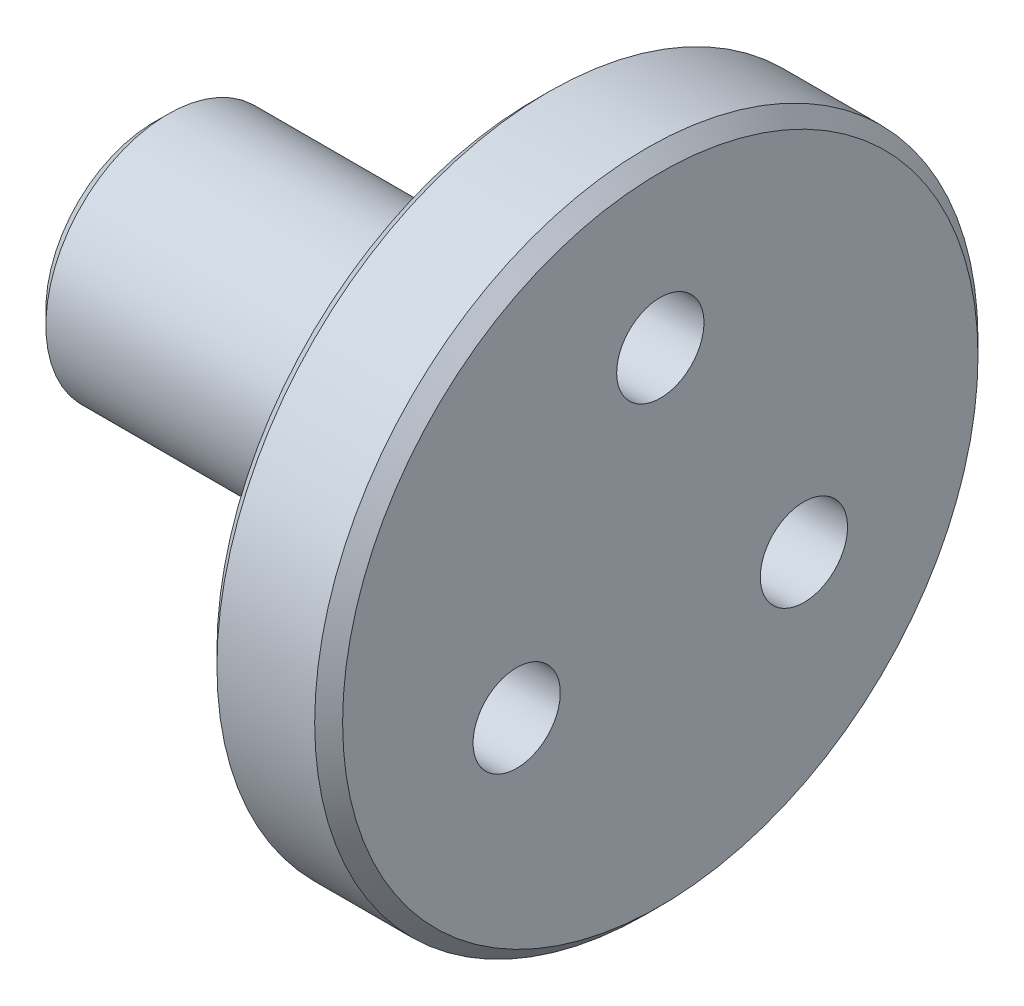
SolidWorks part; units mm, degrees
material "3.0205 (EN-AW 1200)"
ref_plane "Спереди" through (0, 0, 0) normal (0, 0, 1) x (1, 0, 0)
ref_plane "Сверху" through (0, 0, 0) normal (0, 1, 0) x (1, 0, 0)
ref_plane "Справа" through (0, 0, 0) normal (1, 0, 0) x (0, 0, -1)
sketch "Эскиз2" plane through (0, 0, 0) normal (0, 0, 1) x (1, 0, 0)
  line L0 (0, 0) -> (0, 9.5)
  line L1 (0, 9.5) -> (-3.6, 9.5)
  line L2 (-3.6, 9.5) -> (-3.6, 3.5)
  line L3 (-3.6, 3.5) -> (-14.5, 3.5)
  line L4 (-14.5, 3.5) -> (-14.5, 0)
  line L5 (-14.5, 0) -> (0, 0) construction
  line L6 (0, 0) -> (-14.5, 0)
  dimension "D1" = 10.9
  dimension "D2" = 14.5
  dimension "D3" = 3.5
  dimension "D4" = 9.5
revolve "Повернуть1" add sketch "Эскиз2" angle 360 about L5
sketch "Эскиз3" plane through (-3.6, 0, 0) normal (-1, 0, 0) x (0, 0, 1)
  circle A0 centre (0, 4.75) radius 1.25
  circle A1 centre (0, 0) radius 4.75 construction
  dimension "D1" = 2.5
  dimension "D2" = 9.5
extrude "Вырез-Вытянуть1" cut sketch "Эскиз3" against normal through all contours A0
chamfer "Фаска1" distance 0.4 angle 45 3 edges at (-14.5, 0, 3.5) (0, 0, 9.5) (-3.6, 0, 9.5)
pattern_circular "Круговой массив1" count 3 over 360 about axis through (0, 0, 0) along (1, 0, 0) of "Вырез-Вытянуть1"
